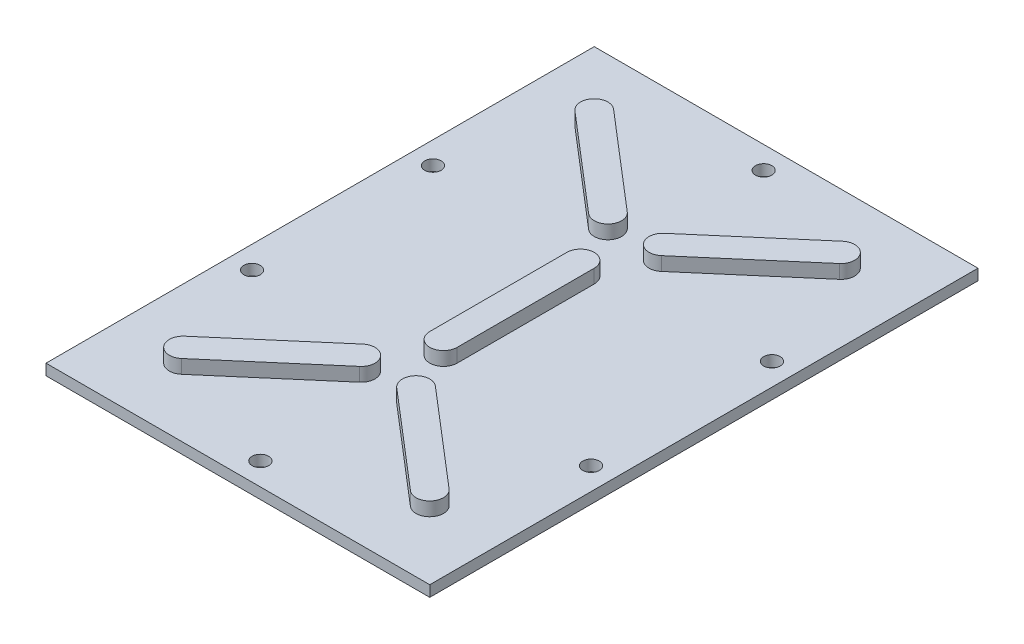
SolidWorks part; units mm, degrees
ref_plane "Front Plane" through (0, 0, 0) normal (0, 0, 1) x (1, 0, 0)
ref_plane "Top Plane" through (0, 0, 0) normal (0, 1, 0) x (1, 0, 0)
ref_plane "Right Plane" through (0, 0, 0) normal (1, 0, 0) x (0, 0, -1)
sketch "Sketch1" plane through (0, 0, 0) normal (0, 1, 0) x (1, 0, 0)
  line L0 (0, 100) -> (140, 100) construction
  line L5 (70, 200) -> (70, 0) construction
  line L6 (80, 55) -> (115, 25) construction
  line L7 (83.254, 58.7963) -> (118.254, 28.7963)
  line L8 (76.746, 51.2037) -> (111.746, 21.2037)
  line L9 (70, 75) -> (70, 125) construction
  line L10 (65, 75) -> (65, 125)
  line L11 (75, 75) -> (75, 125)
  line L12 (60, 55) -> (25, 25) construction
  line L13 (56.746, 58.7963) -> (21.746, 28.7963)
  line L14 (63.254, 51.2037) -> (28.254, 21.2037)
  line L15 (60, 145) -> (25, 175) construction
  line L16 (56.746, 141.2037) -> (21.746, 171.2037)
  line L17 (63.254, 148.7963) -> (28.254, 178.7963)
  line L18 (80, 145) -> (115, 175) construction
  line L19 (83.254, 141.2037) -> (118.254, 171.2037)
  line L20 (76.746, 148.7963) -> (111.746, 178.7963)
  arc A0 (83.254, 58.7963) -> (76.746, 51.2037) centre (80, 55) ccw
  arc A1 (111.746, 21.2037) -> (118.254, 28.7963) centre (115, 25) ccw
  arc A2 (65, 75) -> (75, 75) centre (70, 75) ccw
  arc A3 (75, 125) -> (65, 125) centre (70, 125) ccw
  arc A4 (56.746, 58.7963) -> (63.254, 51.2037) centre (60, 55) cw
  arc A5 (28.254, 21.2037) -> (21.746, 28.7963) centre (25, 25) cw
  arc A6 (56.746, 141.2037) -> (63.254, 148.7963) centre (60, 145) ccw
  arc A7 (28.254, 178.7963) -> (21.746, 171.2037) centre (25, 175) ccw
  arc A8 (83.254, 141.2037) -> (76.746, 148.7963) centre (80, 145) cw
  arc A9 (111.746, 178.7963) -> (118.254, 171.2037) centre (115, 175) cw
  point P11 (97.5, 40)
  point P18 (70, 100)
  point P25 (42.5, 40)
  point P32 (42.5, 160)
  point P39 (97.5, 160)
  dimension "D3" = 5
  dimension "D4" = 5
  dimension "D5" = 0
  dimension "D6" = 50
sketch "Sketch2" plane through (0, 0, 0) normal (0, 1, 0) x (1, 0, 0)
  line L5 (0, 0) -> (140, 0)
  line L6 (0, 0) -> (0, 200)
  line L7 (0, 200) -> (140, 200)
  line L8 (140, 0) -> (140, 200)
  dimension "D1" = 200
  dimension "D2" = 140
extrude "Boss-Extrude1" add sketch "Sketch2" against normal blind 4
extrude "Boss-Extrude2" add sketch "Sketch1" along normal blind 5
sketch "Sketch4" plane through (0, 0, 0) normal (0, 1, 0) x (1, 0, 0)
  line L0 (0, 100) -> (140, 100) construction
  line L3 (70, 0) -> (70, 200) construction
  circle A0 centre (70, 191.8) radius 3
  circle A2 centre (8.1661, 133) radius 3
  circle A3 centre (70, 8.2) radius 3
  circle A4 centre (8.1661, 67) radius 3
  circle A5 centre (131.8339, 67) radius 3
  circle A6 centre (131.8339, 133) radius 3
  dimension "D1" = 6
  dimension "D3" = 8.1661
  dimension "D6" = 6
  dimension "D2" = 33
extrude "Cut-Extrude1" cut sketch "Sketch4" against normal blind 10
